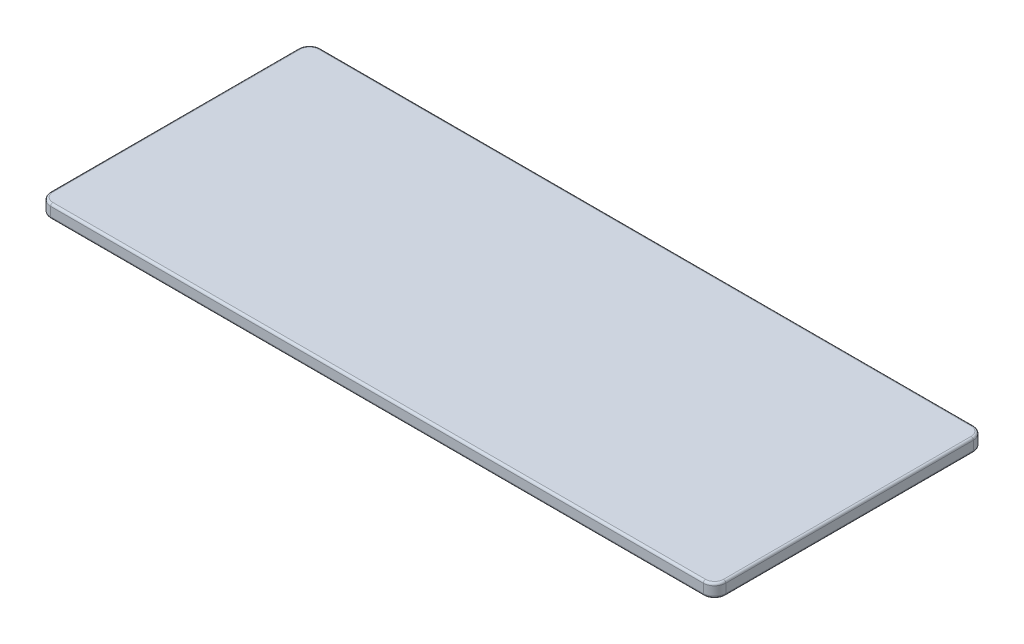
SolidWorks part; units mm, degrees
ref_plane "前视基准面" through (0, 0, 0) normal (0, 0, 1) x (1, 0, 0)
ref_plane "上视基准面" through (0, 0, 0) normal (0, 1, 0) x (1, 0, 0)
ref_plane "右视基准面" through (0, 0, 0) normal (1, 0, 0) x (0, 0, -1)
other "Configuration Table"
sketch "草图1" plane through (0, 0, 0) normal (0, 1, 0) x (1, 0, 0)
  line L1 (-750, 300) -> (750, 300)
  line L2 (-750, 300) -> (-750, -300)
  line L3 (-750, -300) -> (750, -300)
  line L4 (750, 300) -> (750, -300)
  line L5 (-750, 300) -> (750, -300) construction
  line L6 (-750, -300) -> (750, 300) construction
  point P0 (0, 0)
  dimension "D1" = 600
  dimension "D2" = 1500
extrude "凸台-拉伸1" add sketch "草图1" along normal blind 30
fillet "圆角1" radius 25 4 edges at (750, 15, -300) (750, 15, 300) (-750, 15, -300) (-750, 15, 300)
fillet "圆角2" radius 5 16 edges at (-742.6777, 0, -292.6777) (-750, 0, 0) (-742.6777, 0, 292.6777) (0, 0, 300) (742.6777, 0, 292.6777) (750, 0, 0) (742.6777, 0, -292.6777) (0, 0, -300) (742.6777, 30, 292.6777) (0, 30, 300) (-742.6777, 30, 292.6777) (-750, 30, 0) (-742.6777, 30, -292.6777) (0, 30, -300) (742.6777, 30, -292.6777) (750, 30, 0)
